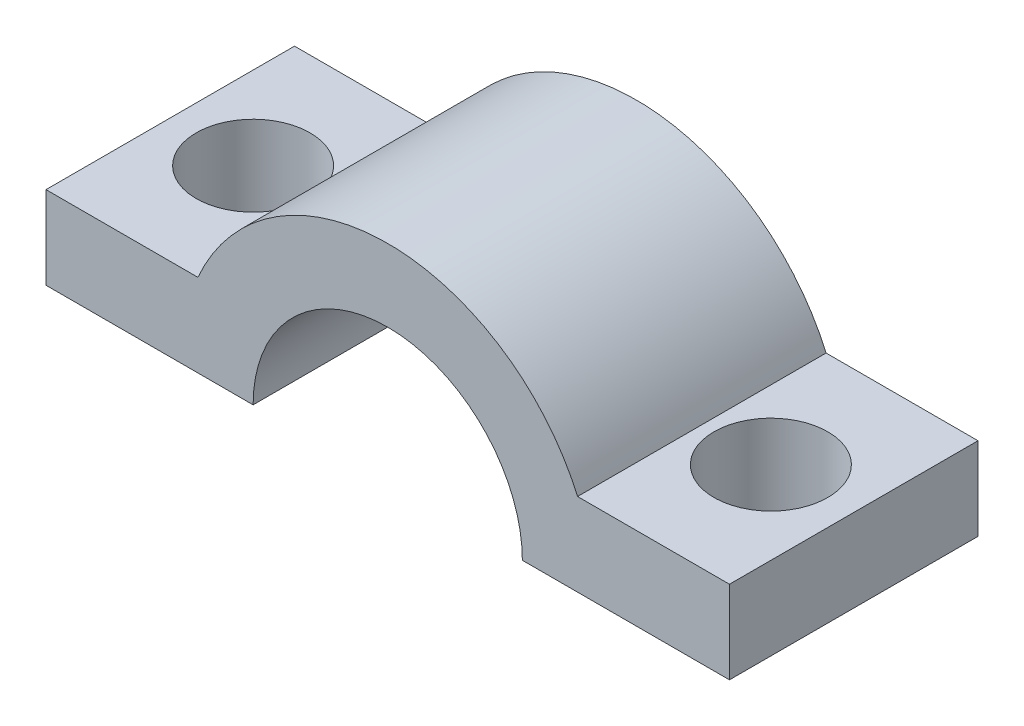
SolidWorks part; units mm, degrees
ref_plane "前视基准面" through (0, 0, 0) normal (0, 0, 1) x (1, 0, 0)
ref_plane "上视基准面" through (0, 0, 0) normal (0, 1, 0) x (1, 0, 0)
ref_plane "右视基准面" through (0, 0, 0) normal (1, 0, 0) x (0, 0, -1)
other "Configuration Table"
sketch "草图1" plane through (0, 0, 0) normal (0, 0, 1) x (1, 0, 0)
  line L0 (-314.0339, 0) -> (15387.6597, 0) construction
  line L1 (0, -314.0339) -> (0, 15387.6597) construction
  line L2 (-33, 0) -> (-33, 8)
  line L3 (13, 0) -> (33, 0)
  line L5 (18.3303, 8) -> (33, 8)
  line L6 (33, 0) -> (33, 8)
  line L7 (-18.3303, 8) -> (-33, 8)
  line L8 (-13, 0) -> (-33, 0)
  arc A0 (13, 0) -> (-13, 0) centre (0, 0) ccw
  arc A1 (18.3303, 8) -> (-18.3303, 8) centre (0, 0) ccw
  dimension "D1" = 13
  dimension "D2" = 20
  dimension "D3" = 8
  dimension "D4" = 66
extrude "凸台-拉伸1" add sketch "草图1" along normal mid plane 24
sketch "草图2" plane through (0, 8, 0) normal (0, 1, 0) x (1, 0, 0)
  line L0 (-1000, 0) -> (49000, 0) construction
  line L1 (0, -1000) -> (0, 49000) construction
  circle A0 centre (25, 0) radius 5.5
  circle A1 centre (-25, 0) radius 5.5
  dimension "D1" = 11
  dimension "D2" = 50
extrude "切除-拉伸1" cut sketch "草图2" against normal through all
